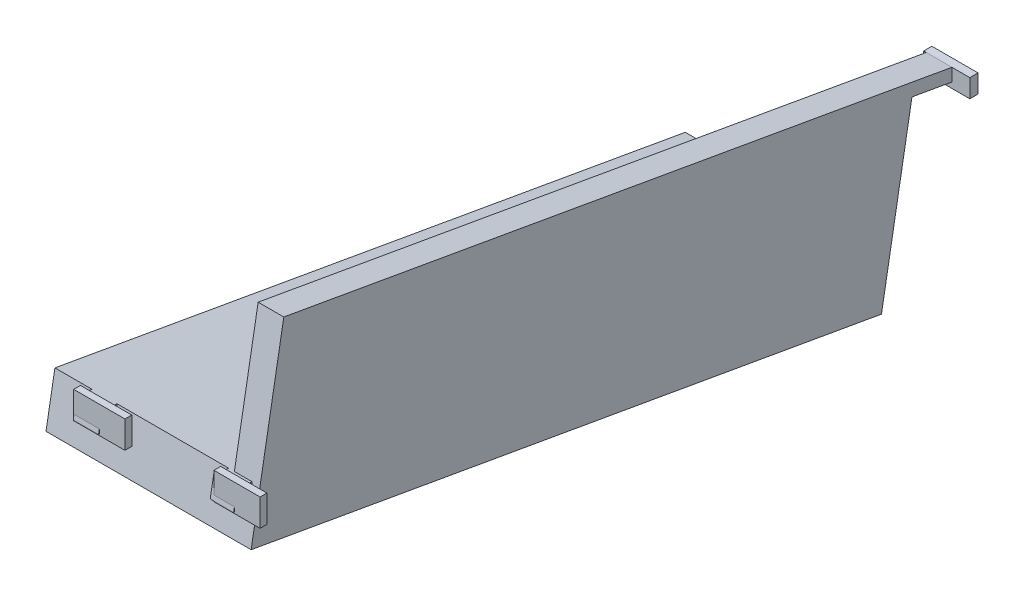
SolidWorks part; units mm, degrees
ref_plane "Front Plane" through (0, 0, 0) normal (0, 0, 1) x (1, 0, 0)
ref_plane "Top Plane" through (0, 0, 0) normal (0, 1, 0) x (1, 0, 0)
ref_plane "Right Plane" through (0, 0, 0) normal (1, 0, 0) x (0, 0, -1)
sketch "Sketch1" plane through (0, 0, 0) normal (1, 0, 0) x (0, 0, -1)
  line L0 (0, 0) -> (1229.237, -216.7477)
  line L1 (1229.237, -216.7477) -> (1211.8722, -315.2284)
  line L2 (1211.8722, -315.2284) -> (-17.3648, -98.4808)
  line L3 (-17.3648, -98.4808) -> (0, 0)
  dimension "D1" = 1248.2
  dimension "D2" = 100
extrude "Boss-Extrude1" add sketch "Sketch1" along normal blind 350
sketch "Sketch2" plane through (350, 0, 0) normal (1, 0, 0) x (0, 0, -1)
  line L0 (-17.3648, -98.4808) -> (46.3384, 262.798)
  line L1 (46.3384, 262.798) -> (1275.5754, 46.0503)
  line L2 (1211.8722, -315.2284) -> (1275.5754, 46.0503)
  line L3 (-17.3648, -98.4808) -> (1211.8722, -315.2284)
extrude "Boss-Extrude2" add sketch "Sketch2" along normal blind 50
sketch "Sketch3" plane through (0, -216.7477, -1229.237) normal (0, -0.1736, -0.9848) x (-1, 0, 0)
  line L0 (-350, 0) -> (-350, 266.852) construction
  line L1 (-400, 266.852) -> (-350, 266.852)
  line L2 (-400, 266.852) -> (-400, 242.3439)
  line L3 (-400, 242.3439) -> (-350, 242.3439)
  line L4 (-350, 266.852) -> (-350, 242.3439)
extrude "Boss-Extrude3" add sketch "Sketch3" along normal blind 90
sketch "Sketch4" plane through (0, 0, 0) normal (0, 0.1736, 0.9848) x (1, 0, 0)
  line L0 (350, 0) -> (0, 0) construction
  line L1 (72.3326, 0) -> (121.4665, 0)
  line L2 (72.3326, 0) -> (72.3326, -39.3027)
  line L3 (72.3326, -39.3027) -> (121.4665, -39.3027)
  line L4 (121.4665, 0) -> (121.4665, -39.3027)
  line L6 (339.2529, 0) -> (384.9014, 0)
  line L7 (339.2529, 0) -> (339.2529, -39.3027)
  line L8 (339.2529, -39.3027) -> (384.9014, -39.3027)
  line L9 (384.9014, 0) -> (384.9014, -39.3027)
extrude "Boss-Extrude4" add sketch "Sketch4" along normal blind 30
sketch "Sketch5" plane through (384.9014, 0, 0) normal (1, 0, 0) x (0, 0, -1)
  line L0 (-36.3691, -33.4962) -> (-6.8248, -38.7056) construction
  line L1 (-21.597, -36.1009) -> (-34.8488, -36.1009)
  line L2 (-21.597, -36.1009) -> (-21.597, 16.8907)
  line L3 (-21.597, 16.8907) -> (-34.8488, 16.8907)
  line L4 (-34.8488, -36.1009) -> (-34.8488, 16.8907)
  line L5 (1364.2081, 30.422) -> (46.3384, 262.798) construction
  line L6 (1349.2252, 33.0639) -> (1365.1765, 33.0639)
  line L7 (1349.2252, 33.0639) -> (1349.2252, -2.7659)
  line L8 (1349.2252, -2.7659) -> (1365.1765, -2.7659)
  line L9 (1365.1765, 33.0639) -> (1365.1765, -2.7659)
  line L10 (1365.1497, 18.9584) -> (1365.199, -21.0415) construction
extrude "Boss-Extrude5" add sketch "Sketch5" along normal blind 50 and the other way blind 40
sketch "Sketch6" plane through (121.4665, 0, 0) normal (1, 0, 0) x (0, 0, -1)
  line L1 (-21.597, -36.1009) -> (-34.8488, -36.1009)
  line L2 (-21.597, -36.1009) -> (-21.597, 16.8907)
  line L3 (-21.597, 16.8907) -> (-34.8488, 16.8907)
  line L4 (-34.8488, -36.1009) -> (-34.8488, 16.8907)
extrude "Boss-Extrude6" add sketch "Sketch6" along normal blind 50 and the other way blind 50
